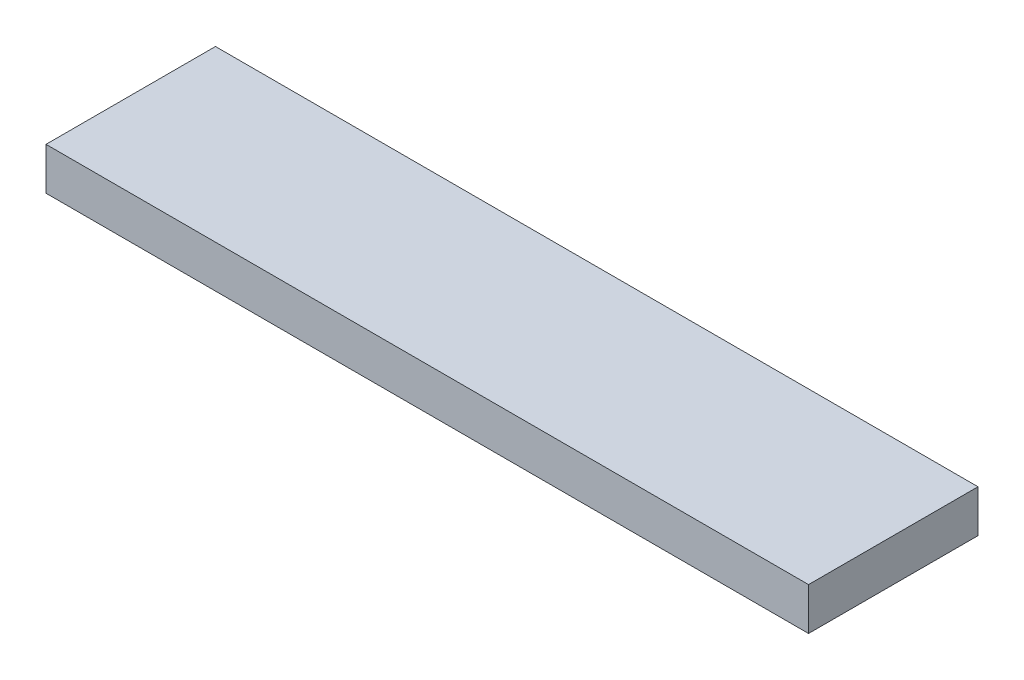
SolidWorks part; units mm, degrees
material "Copper"
ref_plane "Front Plane" through (0, 0, 0) normal (0, 0, 1) x (1, 0, 0)
ref_plane "Top Plane" through (0, 0, 0) normal (0, 1, 0) x (1, 0, 0)
ref_plane "Right Plane" through (0, 0, 0) normal (1, 0, 0) x (0, 0, -1)
sketch "BlockBase" plane through (0, 0, 0) normal (0, 0, 1) x (1, 0, 0)
  line L1 (-114.3, -6.35) -> (114.3, -6.35)
  line L2 (-114.3, -6.35) -> (-114.3, 6.35)
  line L3 (-114.3, 6.35) -> (114.3, 6.35)
  line L4 (114.3, -6.35) -> (114.3, 6.35)
  line L5 (-114.3, -6.35) -> (114.3, 6.35) construction
  line L6 (-114.3, 6.35) -> (114.3, -6.35) construction
  point P0 (0, 0)
  dimension "Length" = 228.6
  dimension "Width" = 12.7
extrude "Block" add sketch "BlockBase" along normal blind 50.8
sketch "Sketch1" [suppressed] plane through (0, 0, 50.8) normal (0, 0, 1) x (1, 0, 0)
  circle A0 centre (0, 0) radius 22.1659
extrude "Cut-Extrude1" [suppressed] cut sketch "Sketch1" against normal through all
